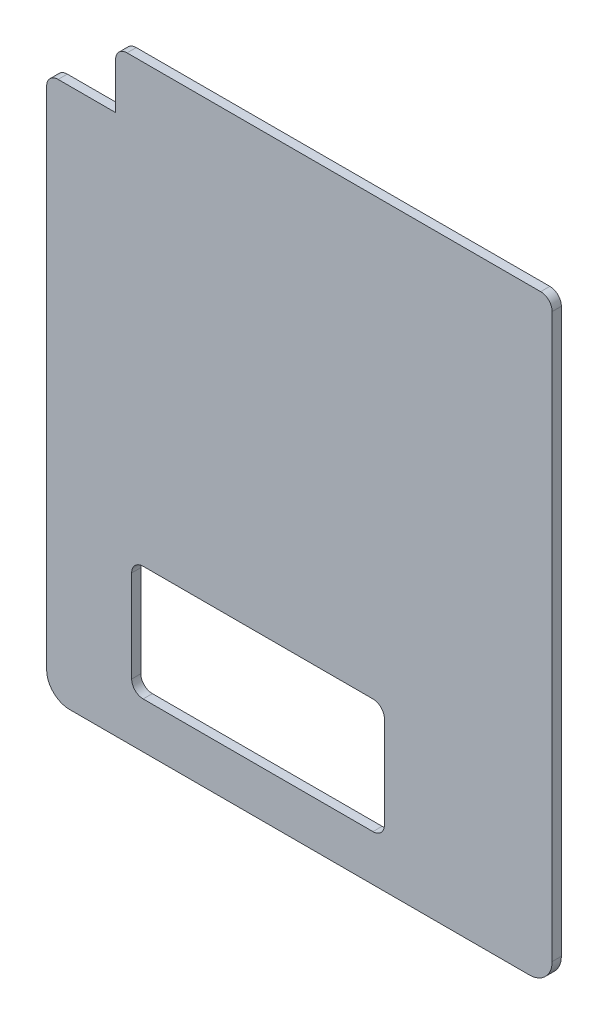
SolidWorks part; units mm, degrees
ref_plane "Ebene vorne" through (0, 0, 0) normal (0, 0, 1) x (1, 0, 0)
ref_plane "Ebene oben" through (0, 0, 0) normal (0, 1, 0) x (1, 0, 0)
ref_plane "Ebene rechts" through (0, 0, 0) normal (1, 0, 0) x (0, 0, -1)
sketch "Skizze1" plane through (0, 0, 0) normal (0, 0, 1) x (1, 0, 0)
  line L0 (0, 0) -> (-19, 0)
  line L1 (-19, 0) -> (-19, -2.5)
  line L2 (-19, -2.5) -> (-22, -2.5)
  line L3 (-22, -2.5) -> (-22, -26)
  line L4 (-22, -26) -> (0, -26)
  line L5 (0, -26) -> (0, 0)
  dimension "D1" = 22
  dimension "D2" = 26
  dimension "D3" = 2.5
  dimension "D4" = 3
extrude "Aufsatz-Linear austragen1" add sketch "Skizze1" along normal blind 0.4
sketch "Skizze2" plane through (0, 0, 0) normal (0, 0, 1) x (1, 0, 0)
  line L0 (-22, -26) -> (0, -26) construction
  line L1 (-18.3, -24) -> (-7.3, -24)
  line L2 (-18.3, -24) -> (-18.3, -19)
  line L3 (-18.3, -19) -> (-7.3, -19)
  line L4 (-7.3, -24) -> (-7.3, -19)
  line L5 (0, -26) -> (0, 0) construction
  line L6 (-22, -2.5) -> (-22, -26) construction
  dimension "D1" = 7
  dimension "D2" = 7.3
  dimension "D3" = 3.7
  dimension "D4" = 2
extrude "Schnitt-Linear austragen1" cut sketch "Skizze2" along normal blind 0.4
fillet "Verrundung1" radius 0.5 7 edges at (0, 0, 0.2) (-22, -2.5, 0.2) (-19, 0, 0.2) (-7.3, -19, 0.2) (-18.3, -19, 0.2) (-18.3, -24, 0.2) (-7.3, -24, 0.2)
fillet "Verrundung2" radius 1 2 edges at (0, -26, 0.2) (-22, -26, 0.2)
other "Körper speichern1"
